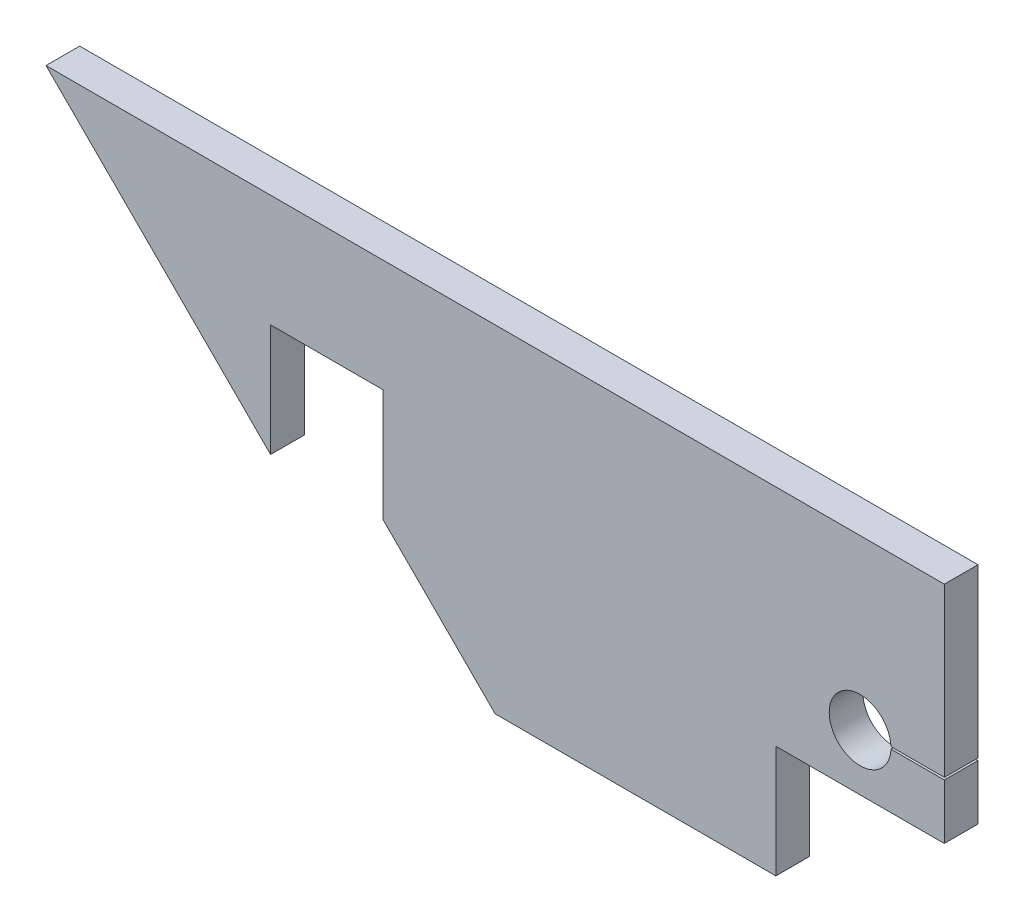
SolidWorks part; units mm, degrees
material "Chapa F.F 1020 - 1,5 mm"
ref_plane "Plano frontal" through (0, 0, 0) normal (0, 0, 1) x (1, 0, 0)
ref_plane "Plano superior" through (0, 0, 0) normal (0, 1, 0) x (1, 0, 0)
ref_plane "Plano direito" through (0, 0, 0) normal (1, 0, 0) x (0, 0, -1)
sketch "Esboço1" plane through (0, 0, 0) normal (0, 0, 1) x (1, 0, 0)
  line L1 (-40, -15) -> (40, -15)
  line L2 (-40, -15) -> (-40, 15)
  line L3 (-40, 15) -> (40, 15)
  line L4 (40, -15) -> (40, 15)
  line L5 (-40, -15) -> (40, 15) construction
  line L6 (-40, 15) -> (40, -15) construction
  point P0 (0, 0)
  dimension "D1" = 80
  dimension "D2" = 30
extrude "Ressalto-extrusão1" add sketch "Esboço1" along normal blind 3
sketch "Esboço3" plane through (0, 0, 3) normal (0, 0, 1) x (1, 0, 0)
  line L0 (-40, -15) -> (40, -15) construction
  line L1 (40, 15) -> (-40, 15) construction
  line L2 (-40, 15) -> (-40, -15)
  line L3 (-40, -15) -> (0, -15)
  line L4 (40, -15) -> (40, 15) construction
  line L11 (-20, -5) -> (-20, 5)
  line L12 (-20, 5) -> (-10, 5)
  line L13 (-10, -5) -> (-10, 5)
  line L14 (25, -15) -> (40, -15)
  line L15 (25, -15) -> (25, -5)
  line L16 (25, -5) -> (40, -5)
  line L17 (40, -15) -> (40, -5)
  line L18 (-20, -5) -> (-40, 15)
  line L19 (0, -15) -> (-10, -5)
  dimension "D1" = 10
  dimension "D2" = 45
  dimension "D3" = 10
  dimension "D4" = 10
  dimension "D5" = 45
  dimension "D6" = 10
  dimension "D7" = 15
  dimension "D8" = 10
extrude "Corte-extrusão1" cut sketch "Esboço3" against normal through all
hole_wizard "Furo com folga de M51" positions "Esboço5" profile "Esboço4" hole size "M5" standard "ISO" end condition through all
sketch "Esboço5" plane through (0, 0, 3) normal (0, 0, 1) x (1, 0, 0)
  line L0 (40, -5) -> (40, 15) construction
  line L3 (0, -15) -> (25, -15) construction
  point P0 (32.5, 0)
  dimension "D1" = 7.5
  dimension "D2" = 15
sketch "Esboço4" plane through (32.5, 0, 3) normal (1, 0, 0) x (0, -1, 0)
  line L0 (0, 0) -> (0, 3)
  line L1 (0, 3) -> (2.75, 3)
  line L2 (2.75, 3) -> (2.75, 0)
  line L5 (2.75, 0) -> (0, 0)
  line L11 (0, -6.35) -> (0, 107.95) construction
  dimension "Thru Hole Dia." = 5.5
  dimension "Thru Hole Depth" = 3
sketch "Esboço6" plane through (0, 0, 3) normal (0, 0, 1) x (1, 0, 0)
  line L0 (40, -5) -> (40, 15) construction
  line L1 (40, 0.1) -> (32.5, 0.1)
  line L2 (40, 0.1) -> (40, -0.1)
  line L3 (40, -0.1) -> (32.5, -0.1)
  line L4 (32.5, 0.1) -> (32.5, -0.1)
  line L5 (32.5, 0) -> (43.3863, 0) construction
  dimension "D1" = 0.2
extrude "Corte-extrusão2" cut sketch "Esboço6" against normal blind 10
